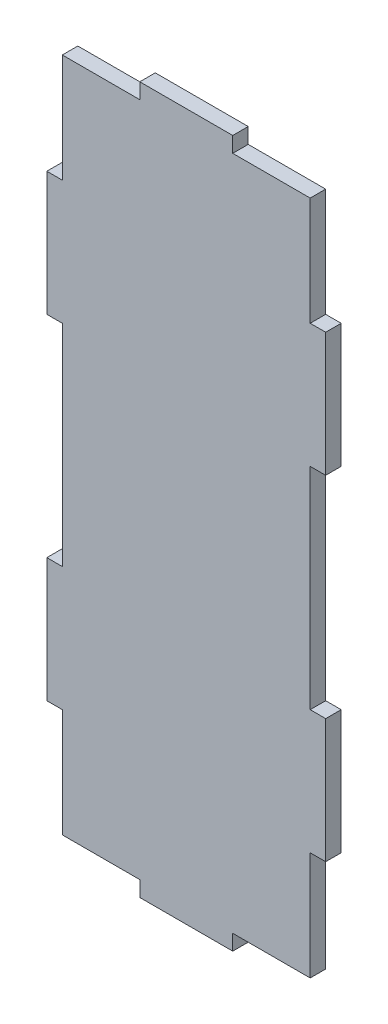
SolidWorks part; units mm, degrees
ref_plane "Front Plane" through (0, 0, 0) normal (0, 0, 1) x (1, 0, 0)
ref_plane "Top Plane" through (0, 0, 0) normal (0, 1, 0) x (1, 0, 0)
ref_plane "Right Plane" through (0, 0, 0) normal (1, 0, 0) x (0, 0, -1)
sketch "Sketch1" plane through (0, 0, 0) normal (0, 0, 1) x (1, 0, 0)
  line L0 (15.875, 138.43) -> (15.875, 141.605)
  line L1 (0, 0) -> (15.875, 0)
  line L2 (0, 0) -> (0, 22.225)
  line L3 (0, 138.43) -> (15.875, 138.43)
  line L4 (50.8, 0) -> (50.8, 22.225)
  line L5 (15.875, 141.605) -> (34.925, 141.605)
  line L6 (34.925, 141.605) -> (34.925, 138.43)
  line L7 (25.4, 141.605) -> (25.4, 144.78) construction
  line L8 (0, 116.205) -> (-3.175, 116.205)
  line L9 (-3.175, 116.205) -> (-3.175, 90.805)
  line L10 (-3.175, 90.805) -> (0, 90.805)
  line L11 (34.925, 138.43) -> (50.8, 138.43)
  line L12 (0, 116.205) -> (0, 138.43)
  line L13 (25.4, 0) -> (25.4, 144.78) construction
  line L14 (50.8, 69.215) -> (0, 69.215) construction
  line L15 (-3.175, 47.625) -> (0, 47.625)
  line L16 (-3.175, 22.225) -> (-3.175, 47.625)
  line L17 (0, 22.225) -> (-3.175, 22.225)
  line L18 (50.8, 22.225) -> (53.975, 22.225)
  line L19 (53.975, 22.225) -> (53.975, 47.625)
  line L20 (53.975, 47.625) -> (50.8, 47.625)
  line L21 (53.975, 90.805) -> (50.8, 90.805)
  line L22 (53.975, 116.205) -> (53.975, 90.805)
  line L23 (50.8, 116.205) -> (53.975, 116.205)
  line L24 (50.8, 116.205) -> (50.8, 138.43)
  line L25 (50.8, 47.625) -> (50.8, 90.805)
  line L26 (0, 47.625) -> (0, 90.805)
  line L27 (34.925, -3.175) -> (34.925, 0)
  line L28 (15.875, 0) -> (15.875, -3.175)
  line L29 (15.875, -3.175) -> (34.925, -3.175)
  line L30 (34.925, 0) -> (50.8, 0)
  dimension "D1" = 138.43
  dimension "D2" = 50.8
  dimension "D3" = 3.175
  dimension "D4" = 19.05
  dimension "D5" = 3.175
  dimension "D6" = 22.225
  dimension "D7" = 25.4
extrude "Boss-Extrude1" add sketch "Sketch1" along normal blind 3.175
